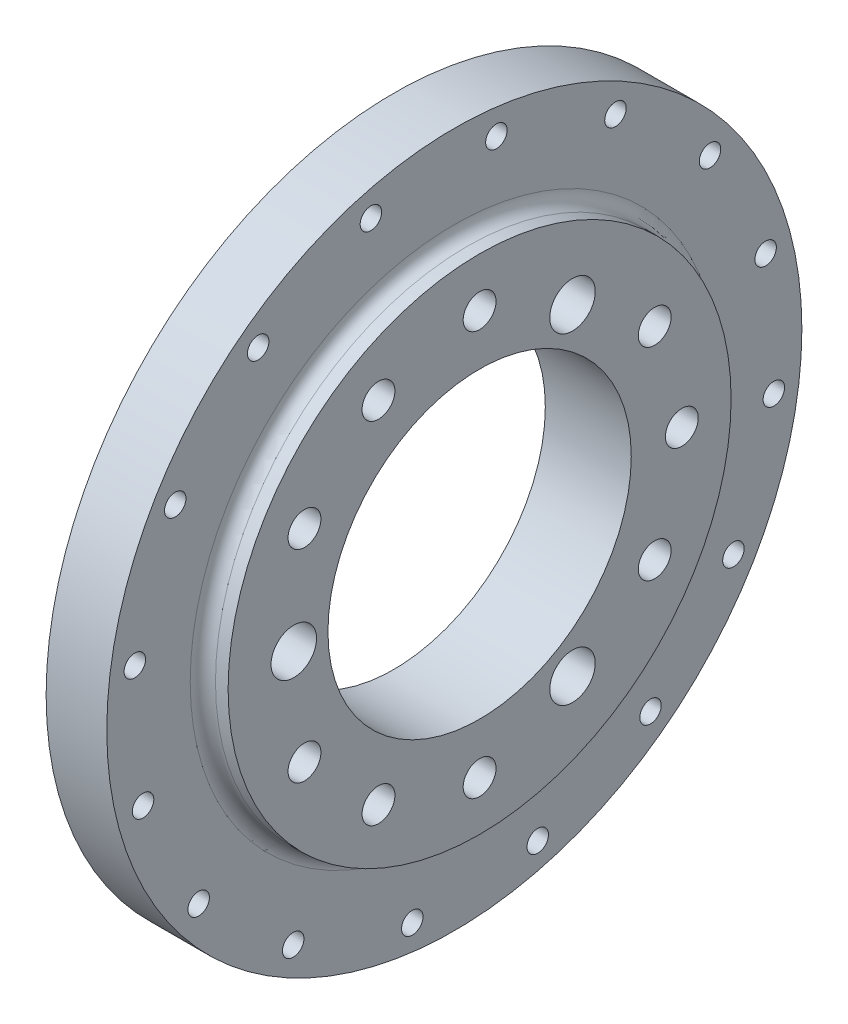
SolidWorks part; units mm, degrees
material "AISI 316 Stainless Steel Sheet (SS)"
ref_plane "Front Plane" through (0, 0, 0) normal (0, 0, 1) x (1, 0, 0)
ref_plane "Top Plane" through (0, 0, 0) normal (0, 1, 0) x (1, 0, 0)
ref_plane "Right Plane" through (0, 0, 0) normal (1, 0, 0) x (0, 0, -1)
sketch "Sketch1" plane through (0, 0, 0) normal (0, 0, 1) x (1, 0, 0)
  line L0 (0, 0) -> (110.2293, 0) construction
  line L1 (24, 137.5) -> (24, 99.5)
  line L2 (0, 60) -> (34, 60)
  line L3 (0, 60) -> (0, 137.5)
  line L4 (0, 137.5) -> (24, 137.5)
  line L5 (34, 60) -> (34, 99.5)
  line L6 (24, 99.5) -> (34, 99.5)
  point P4 (48.839, 60)
  point P10 (45.9521, 81.1862)
  dimension "D1" = 120
  dimension "D2" = 275
  dimension "D3" = 10
  dimension "D4" = 199
  dimension "D5" = 24
revolve "Revolve1" add sketch "Sketch1" angle 360 about L0
sketch "Sketch5" plane through (0, 0, 0) normal (-1, 0, 0) x (0, 0, 1)
  line L0 (0, 0) -> (63.75, -110.4182) construction
  line L1 (0, 0) -> (0, 127.5) construction
  circle A0 centre (0, 0) radius 127.5 construction
  dimension "D1" = 255
  dimension "D2" = 30
hole_wizard "M10 Tapped Hole1" positions "3DSketch2" profile "Sketch6" tap size "M10" standard "ISO"
sketch3d "3DSketch2"
  point P4 (0, -110.4182, 63.75)
sketch "Sketch6" plane through (0, -110.4182, 63.75) normal (0, 1, 0) x (0, 0, 1)
  line L0 (0, 0) -> (0, 41.0537)
  line L1 (0, 41.0537) -> (4.25, 38.5)
  line L2 (4.25, 38.5) -> (4.25, 0.775)
  line L3 (4.25, 0.775) -> (5.025, 0)
  line L5 (5.025, 0) -> (0, 0)
  line L6 (-4.25, 0.775) -> (-5.025, 0) construction
  line L10 (0, 41.0537) -> (-4.25, 38.5) construction
  line L11 (0, -6.35) -> (0, 107.95) construction
  dimension "Tap Drill Dia." = 8.5
  dimension "Tap Drill Depth" = 38.5
  dimension "Near C'Sink Dia." = 10.05
  dimension "Near C'Sink Angle" = 90
  dimension "Drill Angle" = 118
cosmetic thread "Hole Thread10" parameters "D1"=34, "D2"=10
pattern_circular "CirPattern2" count 16 over 360 about axis through (0, 0, 0) along (1, 0, 0) of "M10 Tapped Hole1"
cosmetic thread "Hole Thread11" parameters "D1"=34, "D2"=10
cosmetic thread "Hole Thread12" parameters "D1"=34, "D2"=10
cosmetic thread "Hole Thread13" parameters "D1"=34, "D2"=10
cosmetic thread "Hole Thread14" parameters "D1"=34, "D2"=10
cosmetic thread "Hole Thread15" parameters "D1"=34, "D2"=10
cosmetic thread "Hole Thread16" parameters "D1"=34, "D2"=10
cosmetic thread "Hole Thread17" parameters "D1"=34, "D2"=10
cosmetic thread "Hole Thread18" parameters "D1"=34, "D2"=10
cosmetic thread "Hole Thread19" parameters "D1"=34, "D2"=10
cosmetic thread "Hole Thread20" parameters "D1"=34, "D2"=10
cosmetic thread "Hole Thread21" parameters "D1"=34, "D2"=10
cosmetic thread "Hole Thread22" parameters "D1"=34, "D2"=10
cosmetic thread "Hole Thread23" parameters "D1"=34, "D2"=10
cosmetic thread "Hole Thread24" parameters "D1"=34, "D2"=10
cosmetic thread "Hole Thread25" parameters "D1"=34, "D2"=10
fillet "Fillet1" radius 5 1 edges at (24, 0, 99.5)
sketch "Sketch7" plane through (0, 0, 0) normal (-1, 0, 0) x (0, 0, 1)
  line L0 (0, 0) -> (73.5, 0) construction
  circle A0 centre (0, 0) radius 73.5 construction
  circle A1 centre (73.5, 0) radius 9
  circle A2 centre (-36.75, -63.6529) radius 9
  circle A3 centre (-36.75, 63.6529) radius 9
  point P5 (-73.5, 0)
  point P6 (64.5, 0)
  point P8 (-37.1092, 52.354)
  point P9 (0, 0)
  point P13 (0, 0)
  dimension "D1" = 18
  dimension "D3" = 3
  dimension "D2" = 138
extrude "Cut-Extrude1" cut sketch "Sketch7" against normal through all
sketch "Sketch3" plane through (0, 0, 0) normal (-1, 0, 0) x (0, 0, 1)
  line L0 (0, 0) -> (0, 80) construction
  circle A0 centre (0, 0) radius 80 construction
  circle A1 centre (0, 80) radius 6.5
  circle A2 centre (40, 69.282) radius 6.5
  circle A6 centre (69.282, 40) radius 6.5
  circle A10 centre (80, 0) radius 6.5 [skipped]
  circle A13 centre (69.282, -40) radius 6.5
  circle A14 centre (40, -69.282) radius 6.5
  circle A15 centre (0, -80) radius 6.5
  circle A16 centre (-40, -69.282) radius 6.5 [skipped]
  circle A17 centre (-69.282, -40) radius 6.5
  circle A18 centre (-80, 0) radius 6.5
  circle A19 centre (-69.282, 40) radius 6.5
  circle A20 centre (-40, 69.282) radius 6.5 [skipped]
  point P5 (-69.282, 40)
  point P30 (0, 0)
  dimension "D1" = 160
  dimension "D2" = 13
  dimension "D3" = 12
extrude "Cut-Extrude2" cut sketch "Sketch3" against normal through all
